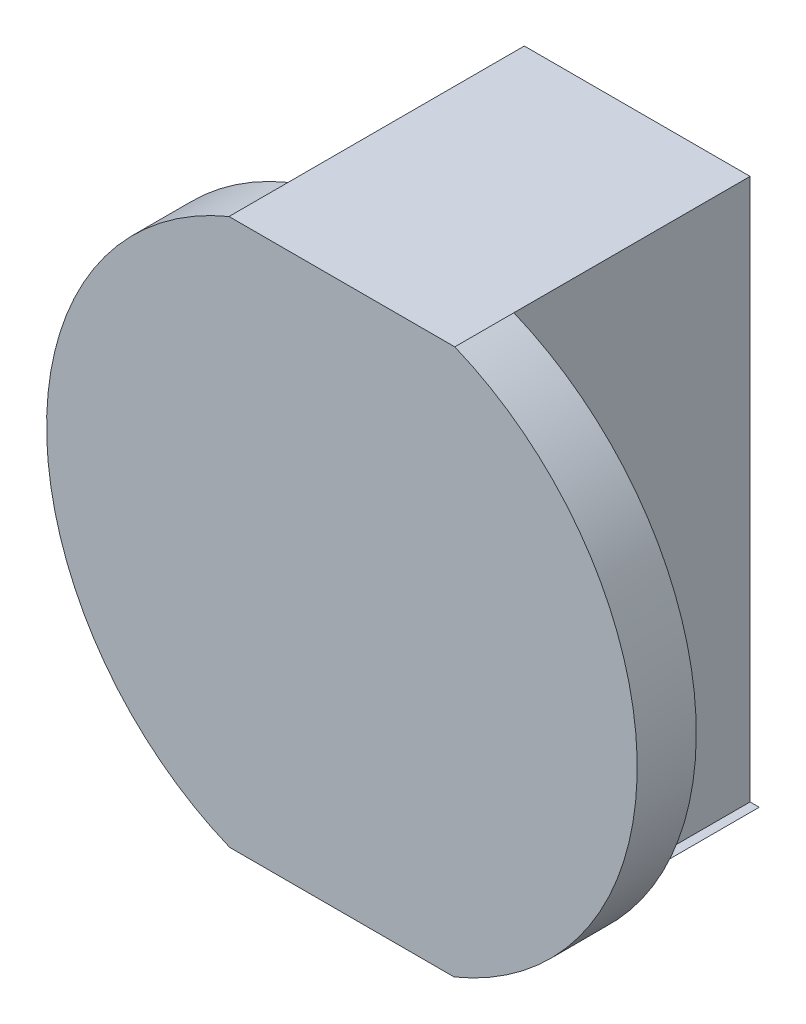
SolidWorks part; units mm, degrees
ref_plane "前视基准面" through (0, 0, 0) normal (0, 0, 1) x (1, 0, 0)
ref_plane "上视基准面" through (0, 0, 0) normal (0, 1, 0) x (1, 0, 0)
ref_plane "右视基准面" through (0, 0, 0) normal (1, 0, 0) x (0, 0, -1)
sketch "草图1" plane through (0, 0, 0) normal (0, 0, 1) x (1, 0, 0)
  circle A0 centre (0, 0) radius 50
extrude "凸台-拉伸1" add sketch "草图1" along normal blind 57.7
sketch "草图2" plane through (0, 0, 57.7) normal (0, 0, 1) x (1, 0, 0)
  line L0 (0, 0) -> (14.2396, 0)
  line L1 (-43.6629, 62.1464) -> (44.8897, 62.1464)
  line L2 (-43.6629, 62.1464) -> (-43.6629, 46.2023)
  line L3 (-43.6629, 46.2023) -> (44.8897, 46.2023)
  line L4 (44.8897, 62.1464) -> (44.8897, 46.2023)
  line L5 (-53.3745, -46.25) -> (80.0497, -46.25)
  line L6 (-53.3745, -46.25) -> (-53.3745, -67.9438)
  line L7 (-53.3745, -67.9438) -> (80.0497, -67.9438)
  line L8 (80.0497, -46.25) -> (80.0497, -67.9438)
extrude "切除-拉伸1" cut sketch "草图2" against normal blind 57.7 contours L2 L1 L4 L3 | L6 L5 L8 L7
sketch "草图3" plane through (0, 0, 0) normal (0, 0, -1) x (-1, 0, 0)
  line L5 (-19.1141, 46.2023) -> (-70.9051, 46.2023)
  line L6 (-19.1141, 46.2023) -> (-19.1141, -45.5301)
  line L7 (-19.1141, -45.5301) -> (-70.9051, -45.5301)
  line L8 (-70.9051, 46.2023) -> (-70.9051, -45.5301)
  line L9 (19.1141, 46.2023) -> (54.5652, 46.2023)
  line L10 (19.1141, 46.2023) -> (19.1141, -50.1019)
  line L11 (19.1141, -50.1019) -> (54.5652, -50.1019)
  line L12 (54.5652, 46.2023) -> (54.5652, -50.1019)
extrude "切除-拉伸2" cut sketch "草图3" against normal blind 40
sketch "草图5" plane through (-19.1141, 0, 0) normal (-1, 0, 0) x (0, 0, 1)
  line L1 (57.7, 46.2023) -> (50, 46.2023)
  line L2 (57.7, 46.2023) -> (57.7, -48.2393)
  line L3 (57.7, -48.2393) -> (50, -48.2393)
  line L4 (50, 46.2023) -> (50, -48.2393)
extrude "切除-拉伸3" cut sketch "草图5" against normal blind 77 and the other way blind 35
